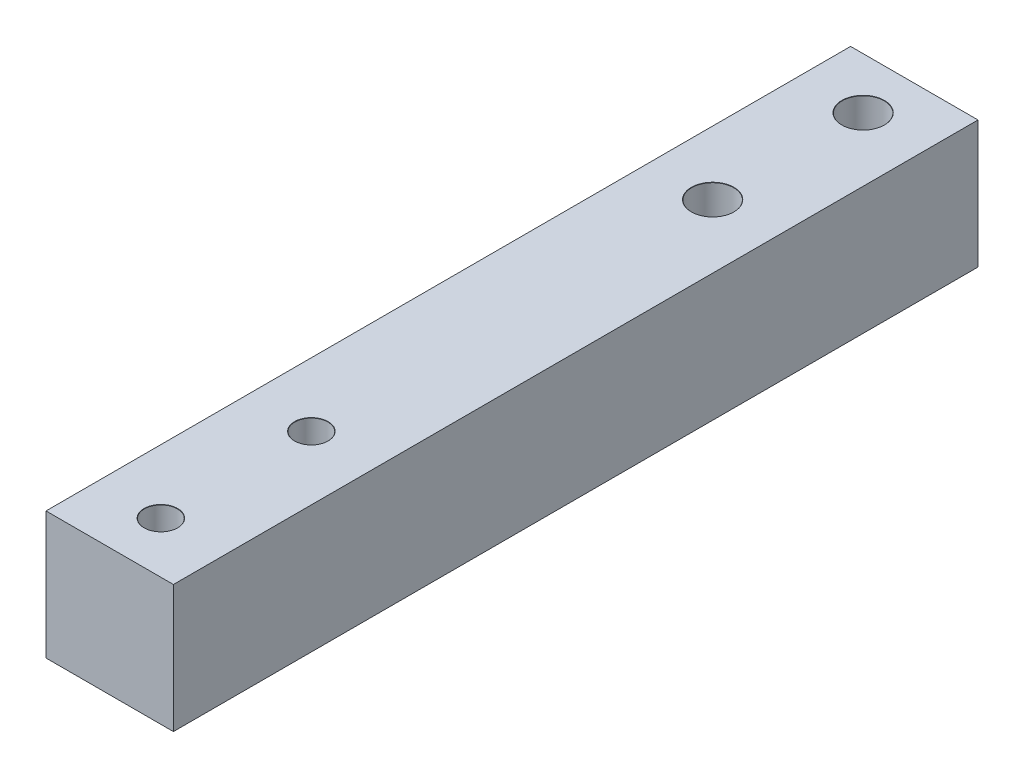
SolidWorks part; units mm, degrees
ref_plane "前基準面" through (0, 0, 0) normal (0, 0, 1) x (1, 0, 0)
ref_plane "上基準面" through (0, 0, 0) normal (0, 1, 0) x (1, 0, 0)
ref_plane "右基準面" through (0, 0, 0) normal (1, 0, 0) x (0, 0, -1)
sketch "草圖1" plane through (0, 0, 0) normal (0, 0, 1) x (1, 0, 0)
  line L1 (6.35, -6.35) -> (-6.35, -6.35)
  line L2 (6.35, -6.35) -> (6.35, 6.35)
  line L3 (6.35, 6.35) -> (-6.35, 6.35)
  line L4 (-6.35, -6.35) -> (-6.35, 6.35)
  line L5 (6.35, -6.35) -> (-6.35, 6.35) construction
  line L6 (6.35, 6.35) -> (-6.35, -6.35) construction
  point P0 (0, 0)
  dimension "D1" = 12.7
extrude "填料-伸長1" add sketch "草圖1" along normal blind 80.2
sketch "草圖2" plane through (0, 6.35, 0) normal (0, 1, 0) x (1, 0, 0)
  line L0 (0, 0) -> (0, -80.2) construction
  line L1 (6.35, -80.2) -> (-6.35, -80.2) construction
  line L2 (-6.35, -40.1) -> (6.35, -40.1) construction
  line L3 (-6.35, -80.2) -> (-6.35, 0) construction
  line L4 (6.35, -80.2) -> (6.35, 0) construction
  point P5 (0, -5.1)
  point P6 (0, -20.1)
  point P7 (0, -60.1)
  point P8 (0, -75.1)
  dimension "D1" = 15
  dimension "D2" = 40
hole_wizard "M4  螺絲攻的螺孔鑽1" positions "草圖3" profile "草圖4" hole size "M4" standard "ISO" end condition through all
sketch "草圖3" plane through (0, 6.35, 0) normal (0, 1, 0) x (1, 0, 0)
  point P8 (0, -60.1)
  point P11 (0, -75.1)
sketch "草圖4" plane through (0, 6.35, 60.1) normal (1, 0, 0) x (0, 0, 1)
  line L0 (0, 0) -> (0, 12.7)
  line L1 (0, 12.7) -> (1.65, 12.7)
  line L2 (1.65, 12.7) -> (1.65, 0.025)
  line L3 (1.65, 0.025) -> (1.675, 0)
  line L5 (1.675, 0) -> (0, 0)
  line L6 (-1.65, 0.025) -> (-1.675, 0) construction
  line L11 (0, -6.35) -> (0, 107.95) construction
  dimension "貫穿孔直徑" = 3.3
  dimension "貫穿孔深度" = 12.7
  dimension "近端錐孔直徑" = 3.35
  dimension "近端錐孔角度" = 90
hole_wizard "M5  螺絲攻的螺孔鑽1" positions "草圖5" profile "草圖6" hole size "M5" standard "ISO" end condition through all
sketch "草圖5" plane through (0, 6.35, 0) normal (0, 1, 0) x (1, 0, 0)
  point P0 (0, -5.1)
  point P3 (0, -20.1)
sketch "草圖6" plane through (0, 6.35, 5.1) normal (1, 0, 0) x (0, 0, 1)
  line L0 (0, 0) -> (0, 12.7)
  line L1 (0, 12.7) -> (2.1, 12.7)
  line L2 (2.1, 12.7) -> (2.1, 0.025)
  line L3 (2.1, 0.025) -> (2.125, 0)
  line L5 (2.125, 0) -> (0, 0)
  line L6 (-2.1, 0.025) -> (-2.125, 0) construction
  line L11 (0, -6.35) -> (0, 107.95) construction
  dimension "貫穿孔直徑" = 4.2
  dimension "貫穿孔深度" = 12.7
  dimension "近端錐孔直徑" = 4.25
  dimension "近端錐孔角度" = 90
